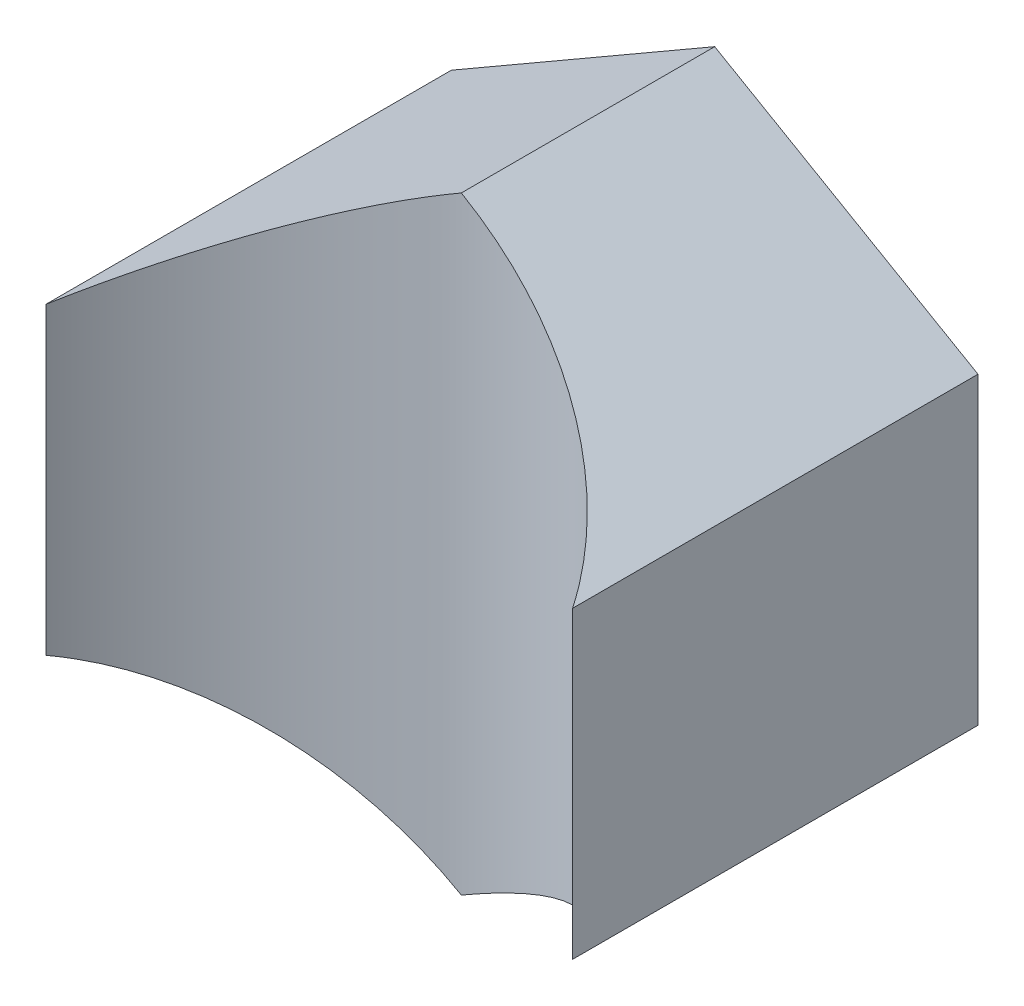
SolidWorks part; units mm, degrees
ref_plane "Front Plane" through (0, 0, 0) normal (0, 0, 1) x (1, 0, 0)
ref_plane "Top Plane" through (0, 0, 0) normal (0, 1, 0) x (1, 0, 0)
ref_plane "Right Plane" through (0, 0, 0) normal (1, 0, 0) x (0, 0, -1)
sketch "Sketch1" plane through (0, 0, 0) normal (0, 0, 1) x (1, 0, 0)
  line L1 (0, -7.5) -> (6.4952, -3.75)
  line L2 (6.4952, -3.75) -> (6.4952, 3.75)
  line L3 (6.4952, 3.75) -> (0, 7.5)
  line L4 (0, 7.5) -> (-6.4952, 3.75)
  line L5 (-6.4952, 3.75) -> (-6.4952, -3.75)
  line L6 (-6.4952, -3.75) -> (0, -7.5)
  circle A0 centre (0, 0) radius 6.4952 construction
  point P1 (0, 0)
  dimension "D1" = 15
extrude "Boss-Extrude1" add sketch "Sketch1" along normal blind 10 contours L5 L6 L1 L2 L3 L4
sketch "Sketch2" plane through (0, 0, 0) normal (0, 1, 0) x (0, 0, -1)
  circle A0 centre (-13.75, 0) radius 7.5
  dimension "D1" = 15
extrude "Cut-Extrude1" cut sketch "Sketch2" against normal mid plane 27
